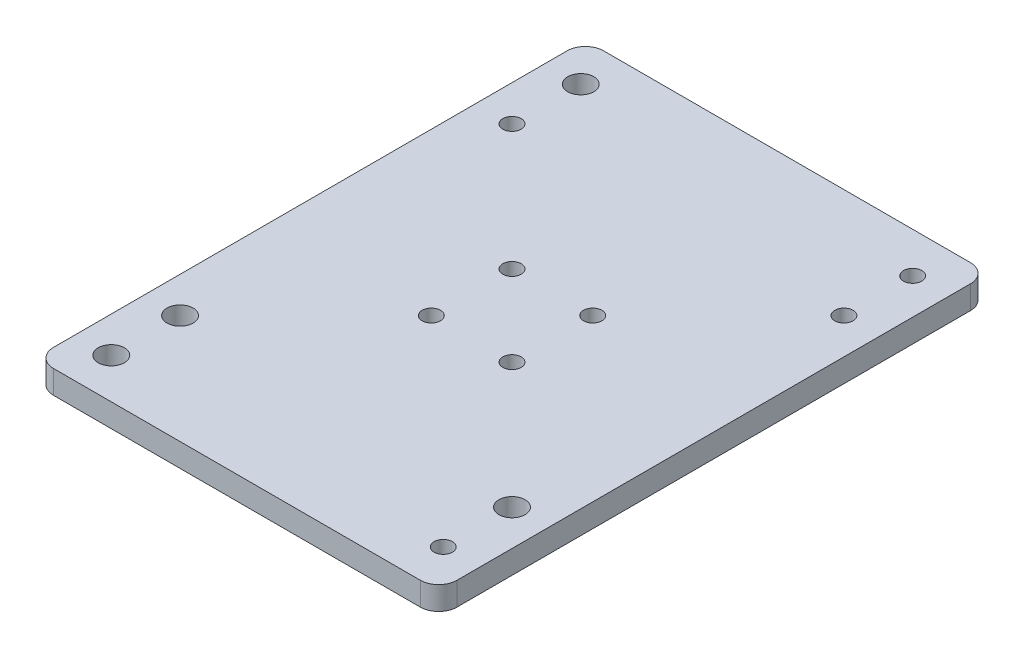
SolidWorks part; units mm, degrees
ref_plane "Front Plane" through (0, 0, 0) normal (0, 0, 1) x (1, 0, 0)
ref_plane "Top Plane" through (0, 0, 0) normal (0, 1, 0) x (1, 0, 0)
ref_plane "Right Plane" through (0, 0, 0) normal (1, 0, 0) x (0, 0, -1)
sketch "Sketch2" plane through (0, 0, 0) normal (0, 1, 0) x (1, 0, 0)
  line L0 (45.25, 45.25) -> (45.25, -45.25) construction
  line L1 (55, -75) -> (-55, -75)
  line L2 (55, -75) -> (55, 75)
  line L3 (55, 75) -> (-55, 75)
  line L4 (-55, -75) -> (-55, 75)
  line L5 (55, -75) -> (-55, 75) construction
  line L6 (55, 75) -> (-55, -75) construction
  line L7 (45.25, -64) -> (-45.25, -64) construction
  line L8 (45.25, -64) -> (45.25, 64) construction
  line L9 (45.25, 64) -> (-45.25, 64) construction
  line L10 (-45.25, -64) -> (-45.25, 64) construction
  line L11 (45.25, -64) -> (-45.25, 64) construction
  line L12 (45.25, 64) -> (-45.25, -64) construction
  line L13 (45.25, 45.25) -> (-45.25, 45.25) construction
  line L14 (-45.25, 45.25) -> (-45.25, -45.25) construction
  line L15 (45.25, -45.25) -> (-45.25, -45.25) construction
  line L16 (45.25, 45.25) -> (-45.25, -45.25) construction
  line L17 (-45.25, 45.25) -> (45.25, -45.25) construction
  line L19 (11, -11) -> (-11, -11) construction
  line L20 (11, -11) -> (11, 11) construction
  line L21 (11, 11) -> (-11, 11) construction
  line L22 (-11, -11) -> (-11, 11) construction
  line L23 (11, -11) -> (-11, 11) construction
  line L24 (11, 11) -> (-11, -11) construction
  circle A0 centre (-45.25, 64) radius 3.56
  circle A1 centre (-45.25, -64) radius 3.56
  circle A2 centre (45.25, 64) radius 2.5
  circle A3 centre (45.25, -64) radius 2.5
  circle A4 centre (-45.25, -45.25) radius 3.56
  circle A5 centre (45.25, -45.25) radius 3.56
  circle A6 centre (-45.25, 45.25) radius 2.5
  circle A7 centre (45.25, 45.25) radius 2.5
  circle A8 centre (-11, 11) radius 2.5
  circle A9 centre (11, 11) radius 2.5
  circle A10 centre (11, -11) radius 2.5
  circle A11 centre (-11, -11) radius 2.5
  point P0 (0, 0)
  point P6 (0, 0)
  point P15 (0, 0)
  point P16 (0, 0)
  point P25 (0, 0)
  dimension "D3" = 7.12
  dimension "D4" = 5
  dimension "D9" = 7.12
  dimension "D10" = 5
  dimension "D12" = 5
  dimension "D1" = 110
  dimension "D2" = 90.5
  dimension "D5" = 90.5
  dimension "D6" = 128
  dimension "D7" = 90.5
  dimension "D8" = 150
  dimension "D11" = 22
extrude "Boss-Extrude1" add sketch "Sketch2" along normal blind 6.35
fillet "Fillet1" radius 5 4 edges at (55, 3.175, -75) (55, 3.175, 75) (-55, 3.175, 75) (-55, 3.175, -75)
